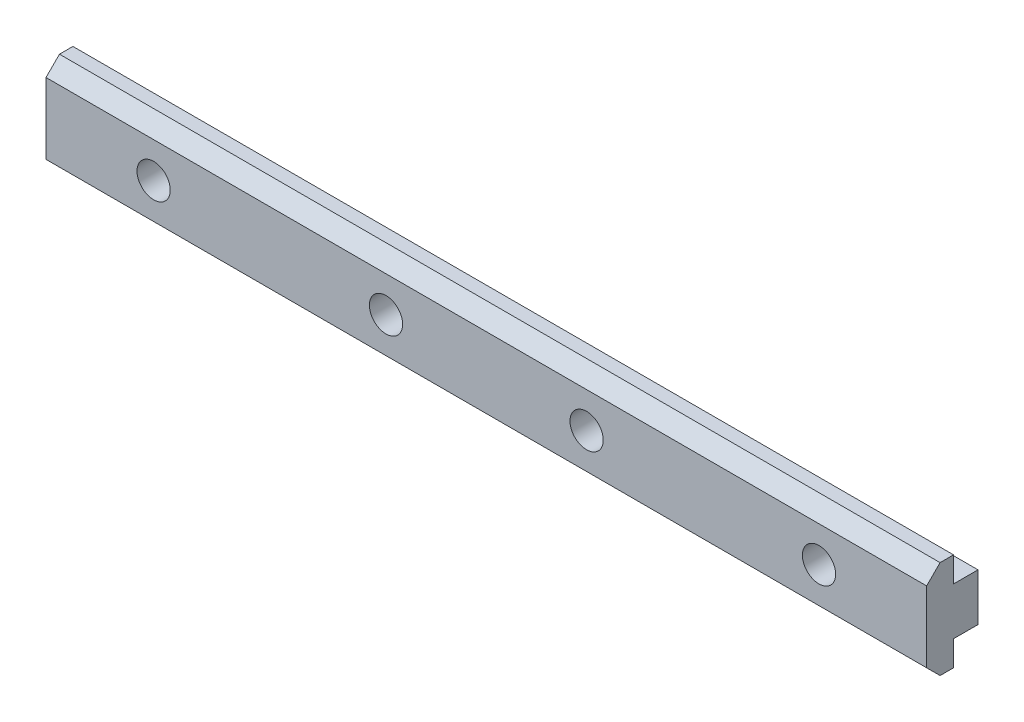
SolidWorks part; units mm, degrees
ref_plane "前视基准面" through (0, 0, 0) normal (0, 0, 1) x (1, 0, 0)
ref_plane "上视基准面" through (0, 0, 0) normal (0, 1, 0) x (1, 0, 0)
ref_plane "右视基准面" through (0, 0, 0) normal (1, 0, 0) x (0, 0, -1)
sketch "草图1" plane through (0, 0, 0) normal (1, 0, 0) x (0, 0, -1)
  line B0 (-10.5, -2.4) -> (-10.5, 12.1)
  line B1 (-5, 14.85) -> (-7.75, 14.85)
  line B2 (-5, -5.15) -> (-7.75, -5.15)
  line B3 (0, 0) -> (0, 9.7)
  line B4 (-5, -5.15) -> (-5, 0)
  line B5 (-5, 9.7) -> (-5, 14.85)
  line B6 (0, 9.7) -> (-5, 9.7)
  line B7 (0, 0) -> (-5, 0)
  line B8 (-7.75, -5.15) -> (-10.5, -2.4)
  line B9 (-7.75, 14.85) -> (-10.5, 12.1)
sketch_block_instance "A$C5E1A1885-1"
sketch_block "A$C5E1A1885"
sketch_block_instance "A$C5E1A1885_0-1"
sketch_block "A$C5E1A1885_0"
extrude "凸台-拉伸1" add sketch "草图1" along normal mid plane 180
sketch "草图4" plane through (0, 0, 0) normal (0, 0, -1) x (-1, 0, 0)
  line L0 (0, -5.15) -> (0, 14.85) construction
  line L1 (-90, -5.15) -> (90, -5.15) construction
  line L2 (-90, 14.85) -> (90, 14.85) construction
  point P6 (-20.5, 4.85)
  point P7 (-68, 4.85)
  point P8 (68, 4.85)
  point P9 (20.5, 4.85)
  dimension "D1" = 20.5
  dimension "D2" = 68
hole_wizard "M8 螺纹孔1" positions "3D草图1" profile "草图5" tap size "M8" standard "Iso"
sketch3d "3D草图1"
  point P0 (68, 4.85, 0)
  point P3 (20.5, 4.85, 0)
  point P6 (-20.5, 4.85, 0)
  point P9 (-68, 4.85, 0)
sketch "草图5" plane through (68, 4.85, 0) normal (1, 0, 0) x (0, 1, 0)
  line L0 (0, 0) -> (0, 35.7929)
  line L1 (0, 35.7929) -> (3.4, 33.75)
  line L2 (3.4, 33.75) -> (3.4, 0)
  line L5 (3.4, 0) -> (0, 0)
  line L10 (0, 35.7929) -> (-3.4, 33.75) construction
  line L11 (0, -6.35) -> (0, 107.95) construction
  dimension "螺纹孔钻头直径" = 6.8
  dimension "螺纹孔钻头深度" = 33.75
  dimension "导头角度" = 118
cosmetic thread "孔螺蚊线1" parameters "D1"=10.5, "D2"=8
cosmetic thread "孔螺蚊线2" parameters "D1"=10.5, "D2"=8
cosmetic thread "孔螺蚊线3" parameters "D1"=10.5, "D2"=8
cosmetic thread "孔螺蚊线4" parameters "D1"=10.5, "D2"=8
